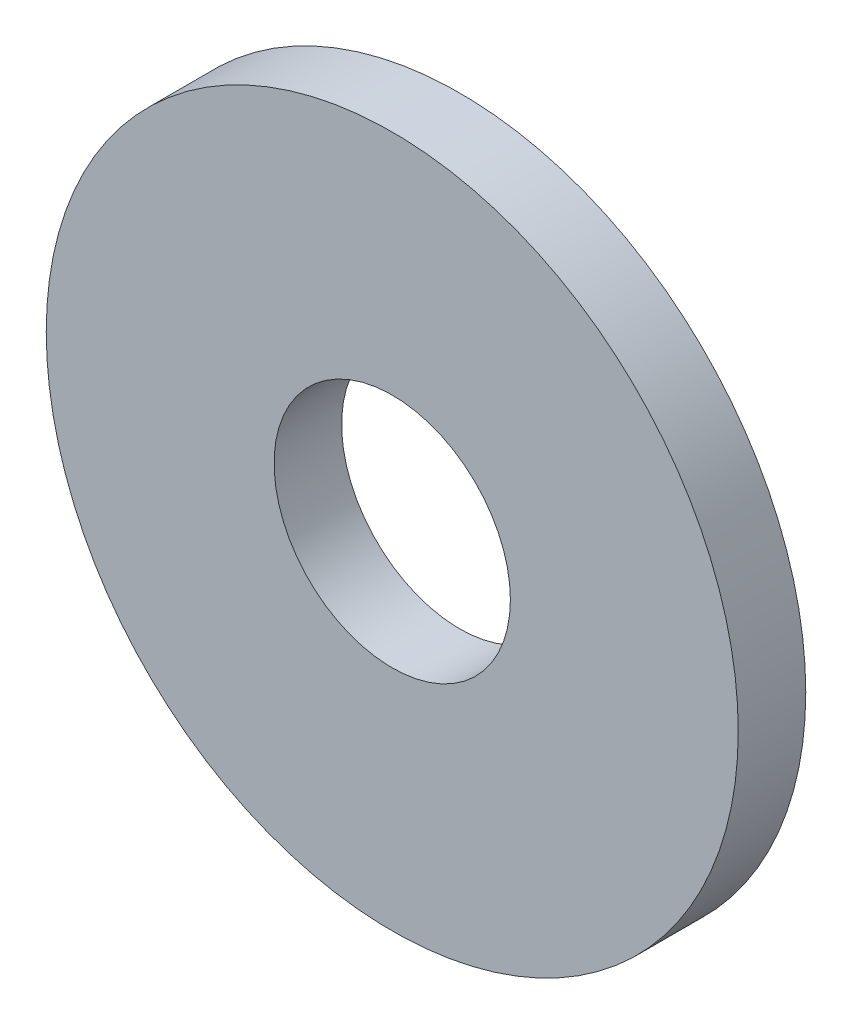
SolidWorks part; units mm, degrees
other "Imported1"
ref_plane "Front Plane" through (0, 0, 0) normal (0, 0, 1) x (1, 0, 0)
ref_plane "Top Plane" through (0, 0, 0) normal (0, 1, 0) x (1, 0, 0)
ref_plane "Right Plane" through (0, 0, 0) normal (1, 0, 0) x (0, 0, -1)
sketch "Sketch1" plane through (0, 0, 0) normal (0, 0, 1) x (1, 0, 0)
  line L0 (-5.207, 0) -> (5.207, 0) construction
  line L1 (-1.778, 0) -> (1.778, 0) construction
  circle A0 centre (0, 0) radius 1.778 construction
  circle A1 centre (0, 0) radius 5.207 construction
  point P8 (0, 0)
  point P9 (0, 5.207)
  point P11 (1.778, 0)
  dimension "ID" = 3.556
  dimension "OD" = 10.414
sketch "Sketch2" plane through (0, 0, 0) normal (1, 0, 0) x (0, 0, -1)
  line L0 (-0.508, 5.207) -> (0.508, 5.207) construction
  point P2 (0, 5.207)
  dimension "Thickness Range" = 1.016
sketch "Sketch3" plane through (0, 0, 0) normal (0, 0, 1) x (1, 0, 0)
  circle A0 centre (0, 0) radius 1.778
  circle A1 centre (0, 0) radius 5.207
extrude "Boss-Extrude1" add sketch "Sketch3" along normal up to vertex (0.508 mm away) and the other way up to vertex (0.508 mm away) up to point (0, 5.207, 0.508) other way up to point (0, 5.207, -0.508)
